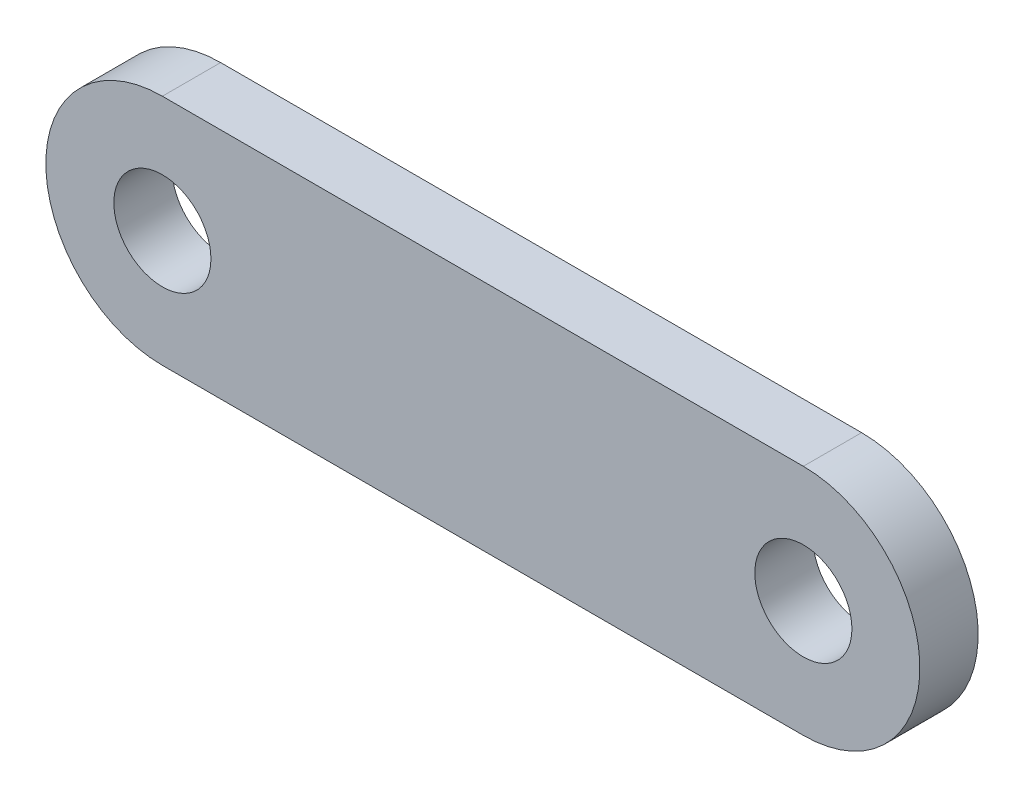
SolidWorks part; units mm, degrees
ref_plane "前视基准面" through (0, 0, 0) normal (0, 0, 1) x (1, 0, 0)
ref_plane "上视基准面" through (0, 0, 0) normal (0, 1, 0) x (1, 0, 0)
ref_plane "右视基准面" through (0, 0, 0) normal (1, 0, 0) x (0, 0, -1)
sketch "草图1" plane through (0, 0, 0) normal (0, 0, 1) x (1, 0, 0)
  line L0 (-497.1836, 0) -> (24361.9946, 0) construction
  line L1 (0, -6) -> (33, -6)
  line L2 (0, 6) -> (33, 6)
  circle A0 centre (0, 0) radius 2.5
  circle A1 centre (0, 0) radius 6
  circle A2 centre (33, 0) radius 2.5
  circle A3 centre (33, 0) radius 6
  dimension "D1" = 12
  dimension "D2" = 5
  dimension "D4" = 33
  dimension "D3" = 2
extrude "凸台-拉伸1" add sketch "草图1" along normal blind 3 contours A1 L0 A3 L2 | L0 A1 L1 A3 | L0 A1 A0 | A1 L0 A0 | A3 L0 A2 | L0 A3 A2
